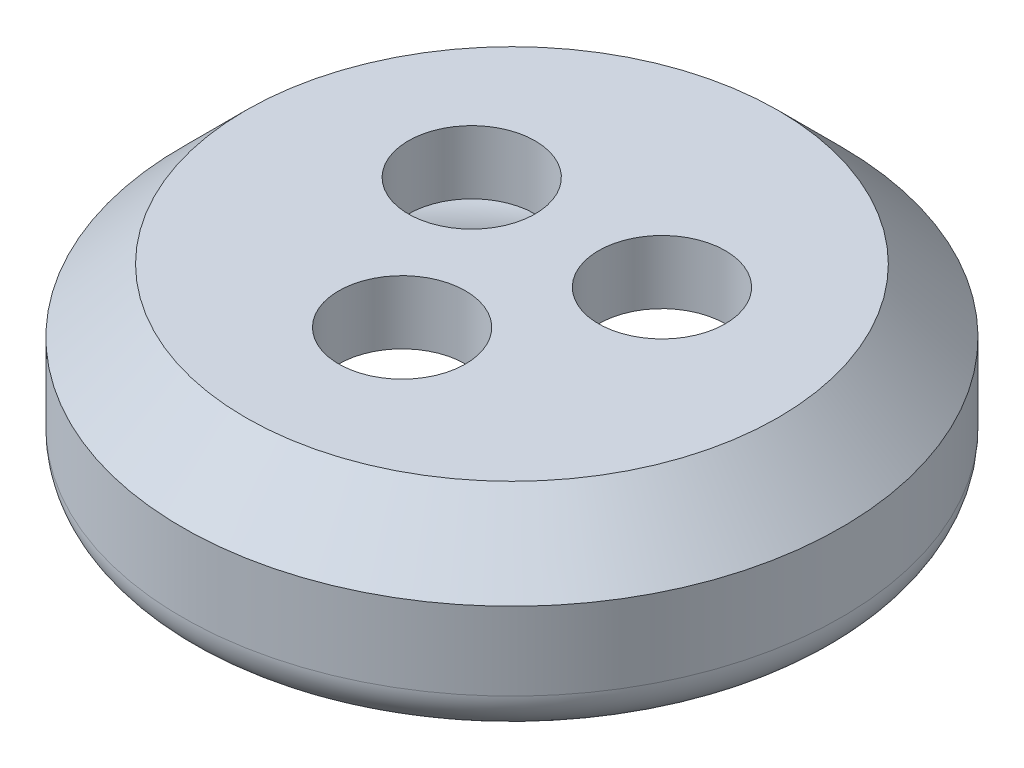
SolidWorks part; units mm, degrees
ref_plane "Front Plane" through (0, 0, 0) normal (0, 0, 1) x (1, 0, 0)
ref_plane "Top Plane" through (0, 0, 0) normal (0, 1, 0) x (1, 0, 0)
ref_plane "Right Plane" through (0, 0, 0) normal (1, 0, 0) x (0, 0, -1)
sketch "Sketch2" plane through (0, 0, 0) normal (0, 0, 1) x (1, 0, 0)
  line L0 (-12.5931, 22.1773) -> (-15.5931, 19.1773)
  line L1 (-7, 29.8952) -> (-1, 29.8952) construction
  line L2 (-7, 29.8952) -> (-7, -2.0096) construction
  line L3 (-7, -2.0096) -> (-1, -2.0096) construction
  line L4 (-1, 29.8952) -> (-1, -2.0096) construction
  line L5 (1, -2.1272) -> (7, -2.1272) construction
  line L6 (1, -2.1272) -> (1, 29.7775) construction
  line L7 (1, 29.7775) -> (7, 29.7775) construction
  line L8 (7, -2.1272) -> (7, 29.7775) construction
  line L9 (0, 0) -> (0, 35.5784) construction
  line L10 (0, 22.1773) -> (-12.5931, 22.1773)
  line L11 (0, 22.1773) -> (0, 19.1773)
  line L20 (-12.5653, 13.4951) -> (-13.5931, 13.4951)
  line L21 (-15.5931, 15.4951) -> (-15.5931, 19.1773)
  line L22 (-9.05, 19.1773) -> (0, 19.1773)
  line L23 (0, 19.1773) -> (0, 22.1773) construction
  line L28 (-9.75, 20.1773) -> (-10.6246, 20.1773)
  line L29 (-9.05, 14.3816) -> (-9.05, 19.4773)
  line L30 (-7.4676, -0.0302) -> (-7.4676, 3.5387)
  line L31 (-17.1033, -31.1846) -> (-7.4676, -0.0302)
  line L32 (-20.2185, -31.1846) -> (-17.1033, -31.1846)
  line L33 (-13.2, 0.0222) -> (-20.2185, -31.1846)
  line L34 (-13.2, 1.7171) -> (-13.2, 0.0222)
  line L35 (-12.5653, 13.4951) -> (-14.8347, 4.3917)
  line L36 (-9.75, 20.1773) -> (-10.6246, 20.1773)
  line L37 (-9.05, 19.1773) -> (-9.05, 19.4773)
  arc A0 (-13.5931, 13.4951) -> (-15.5931, 15.4951) centre (-13.5931, 15.4951) cw
  arc A14 (-9.05, 19.4773) -> (-9.75, 20.1773) centre (-9.75, 19.4773) ccw
  arc A15 (-9.05, 14.3816) -> (-7.4676, 3.5387) centre (2.698, 10.5592) ccw
  arc A16 (-14.8347, 4.3917) -> (-13.2, 1.7171) centre (-12.7, 3.8596) ccw
  arc A17 (-12.5653, 13.4951) -> (-13.4175, 15.8148) centre (-14.7, 14.0273) ccw
  arc A18 (-13.5931, 15.9971) -> (-13.4175, 15.8148) centre (-13.0094, 16.3835) ccw
  arc A19 (-12.9157, 18.8063) -> (-13.5931, 15.9971) centre (-9.4206, 16.4773) ccw
  arc A20 (-10.6246, 20.1773) -> (-12.9157, 18.8063) centre (-10.6246, 17.5773) ccw
  arc A21 (-9.05, 19.4773) -> (-9.75, 20.1773) centre (-9.75, 19.4773) ccw
  arc A24 (-12.5653, 13.4951) -> (-13.4175, 15.8148) centre (-14.7, 14.0273) ccw
  arc A25 (-13.5931, 15.9971) -> (-13.4175, 15.8148) centre (-13.0094, 16.3835) ccw
  arc A26 (-12.9157, 18.8063) -> (-13.5931, 15.9971) centre (-9.4206, 16.4773) ccw
  arc A27 (-10.6246, 20.1773) -> (-12.9157, 18.8063) centre (-10.6246, 17.5773) ccw
  point P16 (-15.5931, 22.1773)
  dimension "D6" = 2
  dimension "D1" = 6
  dimension "D2" = 1
  dimension "D3" = 0.2
  dimension "D4" = 2
  dimension "D5" = 2
  dimension "D7" = 3
revolve "Revolve1" add sketch "Sketch2" angle 360 about L9
sketch "Sketch3" plane through (0, 19.1773, 0) normal (0, -1, 0) x (1, 0, 0)
  line L1 (0, 5.1962) -> (-4.5, -2.5981) construction
  line L2 (-4.5, -2.5981) -> (4.5, -2.5981) construction
  line L3 (4.5, -2.5981) -> (0, 5.1962) construction
  circle A0 centre (-4.5, -2.5981) radius 3
  circle A1 centre (4.5, -2.5981) radius 3
  circle A2 centre (0, 5.1962) radius 3
  circle A3 centre (0, 0) radius 2.5981 construction
  circle A4 centre (0, 5.1962) radius 4 construction
  circle A5 centre (-4.5, -2.5981) radius 4 construction
  circle A6 centre (4.5, -2.5981) radius 4 construction
  dimension "D1" = 6
  dimension "D3" = 8
  dimension "D2" = 9
extrude "Cut-Extrude1" cut sketch "Sketch3" against normal up to next
